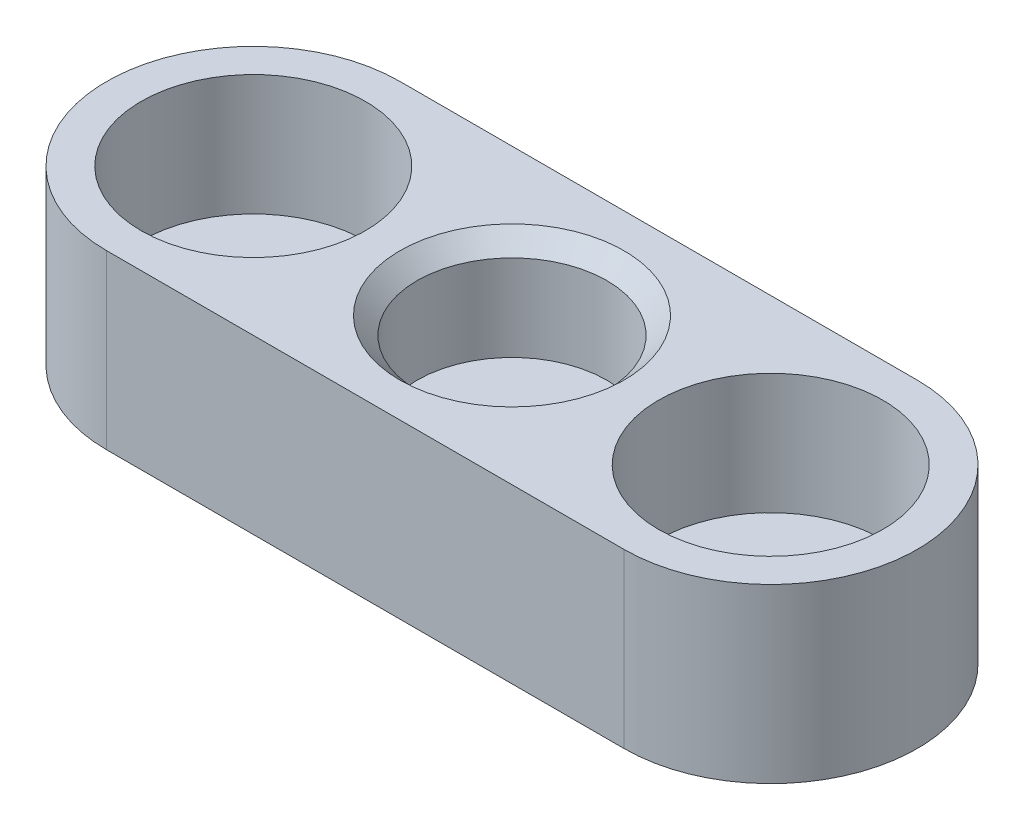
SolidWorks part; units mm, degrees
material "PET"
ref_plane "Front Plane" through (0, 0, 0) normal (0, 0, 1) x (1, 0, 0)
ref_plane "Top Plane" through (0, 0, 0) normal (0, 1, 0) x (1, 0, 0)
ref_plane "Right Plane" through (0, 0, 0) normal (1, 0, 0) x (0, 0, -1)
sketch "Sketch1" plane through (0, 0, 0) normal (0, 1, 0) x (1, 0, 0)
  line L0 (-7.5, 0) -> (7.5, 0) construction
  line L1 (-7.5, 4.25) -> (7.5, 4.25)
  line L4 (7.5, -4.25) -> (-7.5, -4.25)
  circle A0 centre (0, 0) radius 2.75 construction
  arc A1 (-7.5, 4.25) -> (-7.5, -4.25) centre (-7.5, 0) ccw
  arc A2 (7.5, -4.25) -> (7.5, 4.25) centre (7.5, 0) ccw
  circle A5 centre (-7.5, 0) radius 3.25 construction
  dimension "D1" = 5.5
  dimension "D2" = 8.5
  dimension "D4" = 15
  dimension "D5" = 6.5
  dimension "D6" = 1
extrude "Boss-Extrude1" add sketch "Sketch1" along normal blind 5
sketch "Sketch2" plane through (0, 5, 0) normal (0, 1, 0) x (1, 0, 0)
  circle A0 centre (0, 0) radius 2.75
  circle A1 centre (0, 0) radius 2.75 construction
extrude "Cut-Extrude1" cut sketch "Sketch2" against normal blind 3
hole_wizard "CBORE for M3 Hex Socket Head Cap Screw1" positions "Sketch3" profile "Sketch4" counterbore size "M3" standard "ISO" end condition through all
sketch "Sketch3" plane through (0, 5, 0) normal (0, 1, 0) x (1, 0, 0)
  point P0 (-7.5, 0)
  point P3 (7.5, 0)
sketch "Sketch4" plane through (-7.5, 5, 0) normal (1, 0, 0) x (0, 0, 1)
  line L0 (0, 0) -> (0, 5)
  line L1 (0, 5) -> (1.7, 5)
  line L3 (1.7, 5) -> (1.7, 3.5)
  line L4 (1.7, 3.5) -> (3.25, 3.5)
  line L5 (3.25, 3.5) -> (3.25, 0)
  line L7 (3.25, 0) -> (0, 0)
  line L11 (0, -6.35) -> (0, 107.95) construction
  dimension "Thru Hole Dia." = 3.4
  dimension "Thru Hole Depth" = 5
  dimension "C'Bore Dia." = 6.5
  dimension "C'Bore Depth" = 3.5
chamfer "Chamfer1" distance 0.5 angle 45 1 edges at (0, 5, 2.75)
